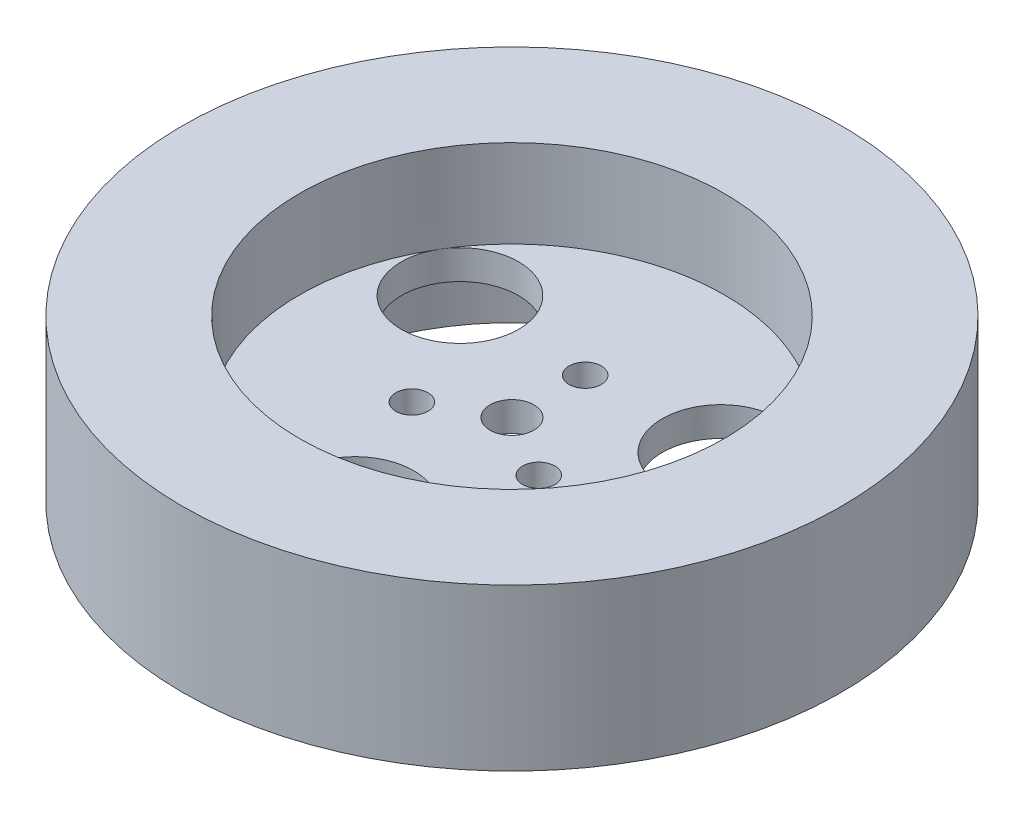
SolidWorks part; units mm, degrees
ref_plane "Front Plane" through (0, 0, 0) normal (0, 0, 1) x (1, 0, 0)
ref_plane "Top Plane" through (0, 0, 0) normal (0, 1, 0) x (1, 0, 0)
ref_plane "Right Plane" through (0, 0, 0) normal (1, 0, 0) x (0, 0, -1)
sketch "Sketch1" plane through (0, 0, 0) normal (0, 1, 0) x (1, 0, 0)
  circle A0 centre (0, 0) radius 22.5
  dimension "D1" = 45
extrude "Boss-Extrude1" add sketch "Sketch1" along normal blind 11
sketch "Sketch2" plane through (0, 11, 0) normal (0, 1, 0) x (1, 0, 0)
  circle A0 centre (0, 0) radius 14.5
  dimension "D1" = 29
extrude "Cut-Extrude1" cut sketch "Sketch2" against normal blind 6
sketch "Sketch3" plane through (0, 0, 0) normal (0, -1, 0) x (1, 0, 0)
  circle A0 centre (0, 0) radius 15
  dimension "D1" = 30
extrude "Cut-Extrude2" cut sketch "Sketch3" against normal blind 3
sketch "Sketch4" plane through (0, 5, 0) normal (0, 1, 0) x (1, 0, 0)
  circle A0 centre (0, 0) radius 1.5
  circle A1 centre (0, 0) radius 5 construction
  circle A2 centre (0, 5) radius 1.1
  circle A3 centre (4.3301, -2.5) radius 1.1
  circle A4 centre (-4.3301, -2.5) radius 1.1
  circle A5 centre (0, 0) radius 14.5 construction
  circle A6 centre (9.1988, 5.0629) radius 4
  circle A7 centre (-0.2148, -10.4978) radius 4
  circle A8 centre (-8.984, 5.4349) radius 4
  point P13 (0, 0)
  point P21 (0, 0)
  dimension "D1" = 3
  dimension "D2" = 2.2
  dimension "D4" = 10
  dimension "D5" = 8
  dimension "D6" = 29
  dimension "D3" = 3
  dimension "D7" = 3
extrude "Cut-Extrude3" cut sketch "Sketch4" against normal up to next contours A6 | A8 | A7 | A0 | A4 | A3 | A2
